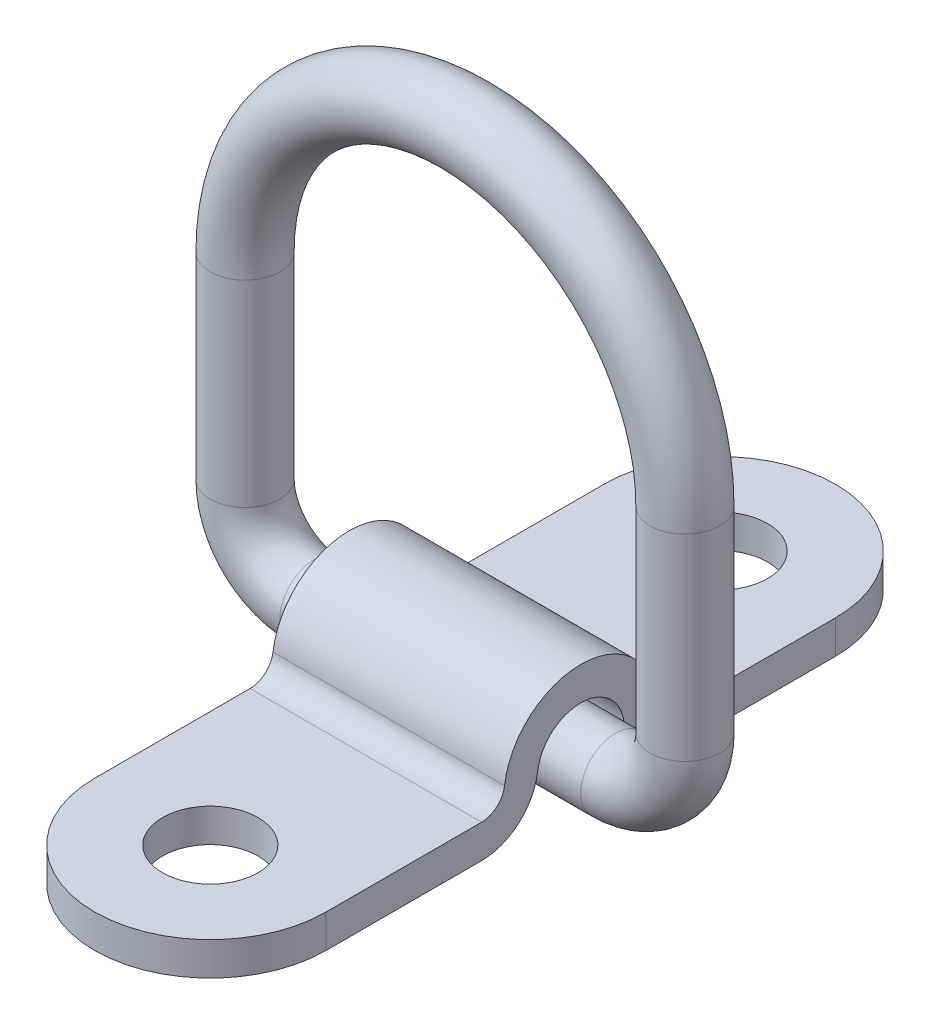
SolidWorks part; units mm, degrees
ref_plane "Front Plane" through (0, 0, 0) normal (0, 0, 1) x (1, 0, 0)
ref_plane "Top Plane" through (0, 0, 0) normal (0, 1, 0) x (1, 0, 0)
ref_plane "Right Plane" through (0, 0, 0) normal (1, 0, 0) x (0, 0, -1)
sketch "Sketch1" plane through (0, 0, 0) normal (0, 0, 1) x (1, 0, 0)
  line L0 (-10.3187, -2.3813) -> (10.3187, -2.3813) construction
  line L1 (0, 0) -> (0, 35.7187) construction
  line L2 (-12.7, 18.2562) -> (-12.7, 4.7625) construction
  line L3 (-15.0813, 18.2562) -> (-15.0812, 4.7625)
  line L4 (-17.4625, 18.2562) -> (-17.4625, 4.7625) construction
  line L5 (17.4625, 18.2562) -> (17.4625, 4.7625) construction
  line L6 (10.3187, 2.3813) -> (-10.3187, 2.3813) construction
  line L7 (12.7, 18.2562) -> (12.7, 4.7625) construction
  line L8 (0, 2.3813) -> (0, -2.3813) construction
  line L9 (15.0813, 18.2562) -> (15.0812, 4.7625)
  line L12 (-10.3187, 0) -> (10.3187, 0)
  arc A0 (17.4625, 18.2562) -> (-17.4625, 18.2562) centre (0, 18.2562) ccw construction
  arc A1 (12.7, 18.2562) -> (-12.7, 18.2562) centre (0, 18.2562) ccw construction
  circle A2 centre (0, 33.3375) radius 2.3812 construction
  circle A3 centre (0, 0) radius 2.3813 construction
  arc A4 (15.0813, 18.2562) -> (-15.0813, 18.2562) centre (0, 18.2562) ccw
  arc A5 (-10.3187, 0) -> (-15.0812, 4.7625) centre (-10.3187, 4.7625) cw
  arc A6 (10.3187, 0) -> (15.0812, 4.7625) centre (10.3187, 4.7625) ccw
  arc A7 (-10.3187, 2.3813) -> (-12.7, 4.7625) centre (-10.3187, 4.7625) cw construction
  arc A8 (-10.3187, -2.3813) -> (-17.4625, 4.7625) centre (-10.3187, 4.7625) cw construction
  arc A9 (10.3187, -2.3813) -> (17.4625, 4.7625) centre (10.3187, 4.7625) ccw construction
  arc A10 (10.3187, 2.3813) -> (12.7, 4.7625) centre (10.3187, 4.7625) ccw construction
  dimension "C" = 4.7625
  dimension "D1" = 4.7625
  dimension "A" = 25.4
  dimension "B" = 38.1
sketch "Sketch2" plane through (0, 0, 0) normal (1, 0, 0) x (0, 0, -1)
  circle A0 centre (0, 0) radius 2.3813
sweep "Sweep1" add profiles "Sketch2" path "Sketch1"
sketch "Sketch3" plane through (0, 0, 0) normal (1, 0, 0) x (0, 0, -1)
  line L0 (-25.4, -2.9845) -> (-6.8001, -2.9845)
  line L1 (-25.4, -2.9845) -> (-25.4, -0.6985)
  line L2 (-25.4, -0.6985) -> (-6.8001, -0.6985)
  line L3 (-25.4, -2.9845) -> (25.4, -2.9845) construction
  line L4 (0, 0) -> (0, -2.9845) construction
  line L5 (25.4, -0.6985) -> (6.8001, -0.6985)
  line L6 (25.4, -2.9845) -> (25.4, -0.6985)
  line L7 (-17.4625, -2.9845) -> (-17.4625, -0.6985) construction
  line L8 (25.4, -2.9845) -> (6.8001, -2.9845)
  circle A0 centre (0, 0) radius 2.9845 construction
  arc A1 (-5.226, 0.6832) -> (5.226, 0.6832) centre (0, 0) cw
  arc A2 (-5.226, 0.6832) -> (-6.8001, -0.6985) centre (-6.8001, 0.889) cw
  arc A3 (-6.8001, -2.9845) -> (-2.9593, 0.3869) centre (-6.8001, 0.889) ccw
  arc A4 (-2.9593, 0.3869) -> (2.9593, 0.3869) centre (0, 0) cw
  arc A5 (6.8001, -2.9845) -> (2.9593, 0.3869) centre (6.8001, 0.889) cw
  arc A6 (5.226, 0.6832) -> (6.8001, -0.6985) centre (6.8001, 0.889) ccw
  circle A7 centre (0, 0) radius 2.9845 construction
  dimension "D1" = 5.969
  dimension "D6" = 1.5875
  dimension "D2" = 2.286
  dimension "D3" = 8.255
  dimension "D4" = 50.8
  dimension "D5" = 34.925
extrude "Boss-Extrude1" add sketch "Sketch3" along normal mid plane 15.875 separate body
sketch "Sketch4" plane through (0, -2.9845, 0) normal (0, -1, 0) x (1, 0, 0)
  line L0 (-7.9375, 17.4625) -> (-7.9375, 25.4)
  line L1 (-7.9375, 25.4) -> (-7.9375, 26.67)
  line L2 (-7.9375, 26.67) -> (7.9375, 26.67)
  line L3 (7.9375, 26.67) -> (7.9375, 25.4)
  line L4 (7.9375, 25.4) -> (7.9375, 17.4625)
  line L5 (7.9375, 25.4) -> (-7.9375, 25.4) construction
  line L6 (-7.9375, 0) -> (7.9375, 0) construction
  line L7 (0, 0) -> (0, 17.4625) construction
  line L8 (7.9375, -25.4) -> (7.9375, -17.4625)
  line L9 (7.9375, -26.67) -> (7.9375, -25.4)
  line L10 (-7.9375, -26.67) -> (7.9375, -26.67)
  line L11 (-7.9375, -25.4) -> (-7.9375, -26.67)
  line L12 (-7.9375, -17.4625) -> (-7.9375, -25.4)
  arc A0 (7.9375, 17.4625) -> (-7.9375, 17.4625) centre (0, 17.4625) ccw
  circle A1 centre (0, 17.4625) radius 3.2766
  circle A2 centre (0, -17.4625) radius 3.2766
  arc A3 (7.9375, -17.4625) -> (-7.9375, -17.4625) centre (0, -17.4625) cw
  dimension "D3" = 6.5532
  dimension "D2" = 1.27
extrude "Cut-Extrude1" cut sketch "Sketch4" against normal through all
